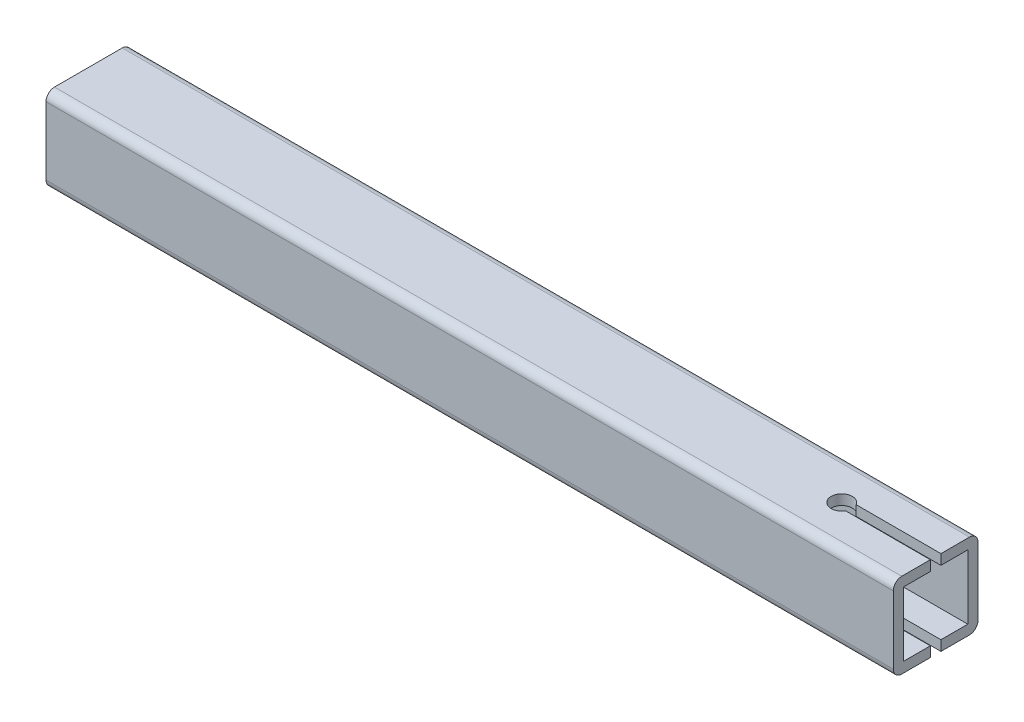
SolidWorks part; units mm, degrees
material "Plain Carbon Steel"
ref_plane "Front Plane" through (0, 0, 0) normal (0, 0, 1) x (1, 0, 0)
ref_plane "Top Plane" through (0, 0, 0) normal (0, 1, 0) x (1, 0, 0)
ref_plane "Right Plane" through (0, 0, 0) normal (1, 0, 0) x (0, 0, -1)
sketch "Sketch1" plane through (0, 0, 0) normal (1, 0, 0) x (0, 0, -1)
  line L0 (0, 2.54) -> (0, 22.86)
  line L1 (-2.54, 25.4) -> (-22.86, 25.4)
  line L2 (-25.4, 22.86) -> (-25.4, 2.54)
  line L3 (-22.86, 0) -> (-2.54, 0)
  line L4 (-3.048, 3.048) -> (-3.048, 22.352)
  line L5 (-3.048, 22.352) -> (-22.352, 22.352)
  line L6 (-22.352, 22.352) -> (-22.352, 3.048)
  line L7 (-22.352, 3.048) -> (-3.048, 3.048)
  arc A0 (-25.4, 2.54) -> (-22.86, 0) centre (-22.86, 2.54) ccw
  arc A1 (0, 2.54) -> (-2.54, 0) centre (-2.54, 2.54) cw
  arc A2 (0, 22.86) -> (-2.54, 25.4) centre (-2.54, 22.86) ccw
  arc A3 (-25.4, 22.86) -> (-22.86, 25.4) centre (-22.86, 22.86) cw
  arc A4 (-3.048, 22.352) -> (-3.048, 22.352) centre (-3.048, 22.352) ccw
  arc A5 (-22.352, 22.352) -> (-22.352, 22.352) centre (-22.352, 22.352) cw
  arc A6 (-22.352, 3.048) -> (-22.352, 3.048) centre (-22.352, 3.048) ccw
  arc A7 (-3.048, 3.048) -> (-3.048, 3.048) centre (-3.048, 3.048) cw
  point P12 (0, 0)
  point P15 (0, 25.4)
  point P18 (-25.4, 25.4)
  dimension "D3" = 2.54
  dimension "D1" = 25.4
  dimension "D2" = 25.4
  dimension "D4" = 3.048
extrude "Boss-Extrude1" add sketch "Sketch1" along normal blind 254
sketch "Sketch2" plane through (0, 25.4, 0) normal (0, 1, 0) x (1, 0, 0)
  line L0 (254, -2.54) -> (254, -22.86) construction
  line L1 (254, -11.1125) -> (228.6, -11.1125)
  line L2 (254, -11.1125) -> (254, -14.2875)
  line L3 (254, -14.2875) -> (228.6, -14.2875)
  line L5 (241.3, -14.2875) -> (241.3, -11.1125) construction
  line L6 (254, -12.7) -> (225.8504, -12.7) construction
  arc A0 (228.6, -11.1125) -> (228.6, -14.2875) centre (225.8504, -12.7) ccw
  point P152 (241.3, -12.7)
  dimension "D3" = 6.35
  dimension "D1" = 3.175
  dimension "D2" = 25.4
extrude "Cut-Extrude1" cut sketch "Sketch2" against normal through all and the other way through all
